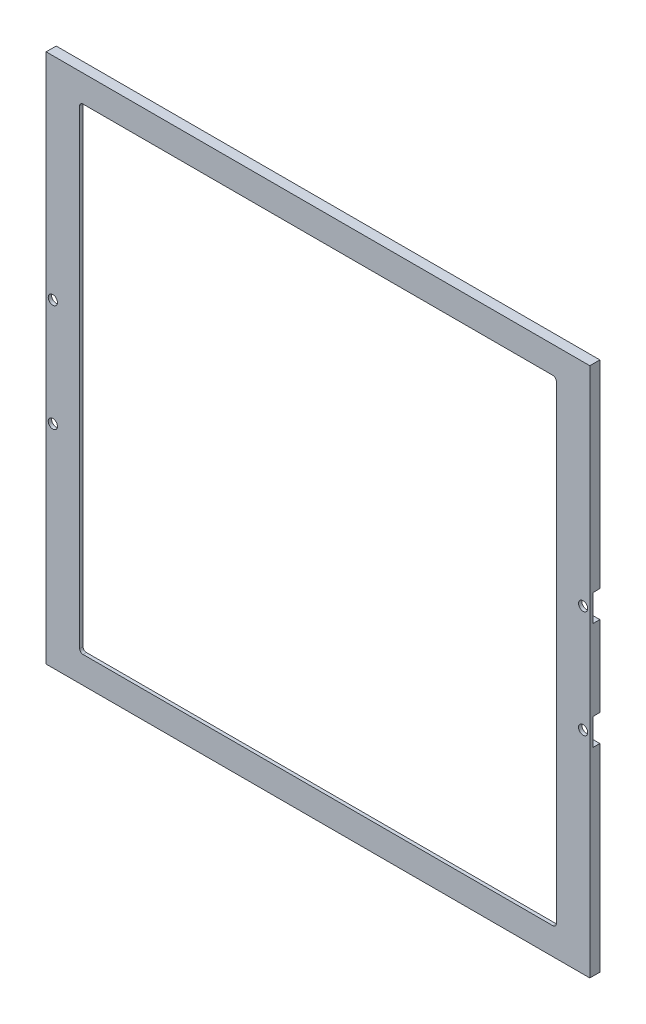
SolidWorks part; units mm, degrees
ref_plane "Front Plane" through (0, 0, 0) normal (0, 0, 1) x (1, 0, 0)
ref_plane "Top Plane" through (0, 0, 0) normal (0, 1, 0) x (1, 0, 0)
ref_plane "Right Plane" through (0, 0, 0) normal (1, 0, 0) x (0, 0, -1)
sketch "Sketch1" plane through (0, 0, 0) normal (0, 0, 1) x (1, 0, 0)
  line L0 (-238.335, 238.335) -> (-238.335, -238.335)
  line L1 (-238.335, -238.335) -> (238.335, -238.335)
  line L2 (238.335, -238.335) -> (238.335, 238.335)
  line L3 (238.335, 238.335) -> (-238.335, 238.335)
  line L4 (237.7, 237.7) -> (-237.7, 237.7)
  line L5 (-237.7, 237.7) -> (-237.7, -237.7)
  line L6 (-237.7, -237.7) -> (237.7, -237.7)
  line L7 (237.7, -237.7) -> (237.7, 237.7)
  line L8 (237.7, 237.7) -> (-237.7, 237.7) construction
  line L9 (-237.7, 237.7) -> (-237.7, -237.7) construction
  line L10 (-237.7, -237.7) -> (237.7, -237.7) construction
  line L11 (237.7, -237.7) -> (237.7, 237.7) construction
  line L12 (251.035, 251.035) -> (-251.035, 251.035)
  line L13 (-251.035, 251.035) -> (-251.035, -251.035)
  line L14 (-251.035, -251.035) -> (251.035, -251.035)
  line L15 (251.035, -251.035) -> (251.035, 251.035)
  dimension "D1" = 0
  dimension "D2" = 0.635
  dimension "D3" = 12.7
extrude "Extrude1" add sketch "Sketch1" against normal blind 6.35
sketch "Sketch2" plane through (0, 0, 0) normal (0, 0, 1) x (1, 0, 0)
  line L0 (251.035, 251.035) -> (-251.035, 251.035) construction
  line L1 (251.035, -251.035) -> (251.035, 251.035) construction
  line L2 (-251.035, -251.035) -> (251.035, -251.035) construction
  line L3 (-251.035, 251.035) -> (-251.035, -251.035) construction
  line L4 (251.035, 251.035) -> (-251.035, 251.035)
  line L5 (251.035, -251.035) -> (251.035, 251.035)
  line L6 (-251.035, -251.035) -> (251.035, -251.035)
  line L7 (-251.035, 251.035) -> (-251.035, -251.035)
  line L8 (-225.635, 225.635) -> (-225.635, -225.635)
  line L9 (-225.635, -225.635) -> (225.635, -225.635)
  line L10 (225.635, -225.635) -> (225.635, 225.635)
  line L11 (225.635, 225.635) -> (-225.635, 225.635)
  dimension "D1" = 25.4
extrude "Extrude2" add sketch "Sketch2" along normal blind 3.175
sketch "Sketch7" plane through (0, 0, 3.175) normal (0, 0, 1) x (1, 0, 0)
  line L0 (-251.035, -251.035) -> (251.035, -251.035) construction
  line L1 (-251.035, 251.035) -> (-257.385, 251.035)
  line L2 (-251.035, 251.035) -> (-251.035, -251.035)
  line L3 (-251.035, -251.035) -> (-257.385, -251.035)
  line L4 (-257.385, 251.035) -> (-257.385, -251.035)
  dimension "D1" = 6.35
extrude "Extrude3" add sketch "Sketch7" against normal up to surface (9.525 mm away) up to face at (0, 0, -6.35)
mirror "Mirror1" about plane through (0, 0, 0) normal (1, 0, 0) of "Extrude3"
hole_wizard "5/16 Clearance Hole1" positions "Sketch6" profile "Sketch5" hole size "5/16" standard "Ansi Inch" end condition through all
sketch "Sketch6" plane through (0, 0, 3.175) normal (0, 0, 1) x (1, 0, 0)
  line L0 (251.035, 0) -> (-251.035, 0) construction
  line L3 (251.035, -50.8) -> (251.035, 50.8) construction
  line L4 (-251.035, -50.8) -> (-251.035, 50.8) construction
  line L5 (-225.635, 225.635) -> (-225.635, -225.635) construction
  line L6 (225.635, -225.635) -> (225.635, 225.635) construction
  point P0 (251.035, -50.8)
  point P1 (251.035, 50.8)
  point P3 (-251.035, -50.8)
  point P5 (-251.035, 50.8)
  dimension "D1" = 25.4
  dimension "D2" = 25.4
  dimension "D3" = 50.8
  dimension "D4" = 101.6
  dimension "D5" = 50.8
  dimension "D6" = 101.6
sketch "Sketch5" plane through (251.035, -50.8, 3.175) normal (1, 0, 0) x (0, -1, 0)
  line L0 (0, 0) -> (0, 9.525)
  line L1 (0, 9.525) -> (4.365, 9.525)
  line L2 (4.365, 9.525) -> (4.365, 0)
  line L5 (4.365, 0) -> (0, 0)
  line L11 (0, -6.35) -> (0, 107.95) construction
  dimension "Thru Hole Dia." = 8.73
  dimension "Thru Hole Depth" = 9.525
sketch "Sketch8" plane through (0, 0, -6.35) normal (0, 0, -1) x (-1, 0, 0)
  line L0 (257.385, -251.035) -> (257.385, 251.035) construction
  line L1 (257.385, 63.5) -> (238.335, 63.5)
  line L2 (257.385, 63.5) -> (257.385, 38.1)
  line L3 (257.385, 38.1) -> (238.335, 38.1)
  line L4 (238.335, 63.5) -> (238.335, 38.1)
  line L5 (238.335, 50.8) -> (257.385, 50.8) construction
  line L6 (238.335, 238.335) -> (238.335, -238.335) construction
  point P8 (251.035, 50.8)
  dimension "D1" = 25.4
extrude "Cut-Extrude1" cut sketch "Sketch8" against normal blind 6.35
pattern_linear "LPattern1" count 2 spacing 101.6 along (0, -1, 0) of "Cut-Extrude1"
mirror "Mirror2" about plane through (0, 0, 0) normal (1, 0, 0) of "LPattern1", "Cut-Extrude1"
sketch "Sketch9" plane through (0, 0, 0) normal (0, 0, -1) x (-1, 0, 0)
  line L0 (-238.335, 238.335) -> (-235.16, 238.335)
  line L1 (-235.16, 238.335) -> (-235.16, 235.16)
  line L2 (0, 0) -> (0, 142.1036) construction
  line L3 (235.16, 238.335) -> (235.16, 235.16)
  line L4 (238.335, 238.335) -> (235.16, 238.335)
  line L5 (0, 0) -> (85.8683, 0) construction
  line L6 (238.335, -238.335) -> (235.16, -238.335)
  line L7 (235.16, -238.335) -> (235.16, -235.16)
  line L8 (-235.16, -238.335) -> (-235.16, -235.16)
  line L9 (-238.335, -238.335) -> (-235.16, -238.335)
  line L10 (-238.335, 238.335) -> (238.335, 238.335) construction
  line L11 (-238.335, 63.5) -> (-238.335, 238.335) construction
  arc A0 (-238.335, 238.335) -> (-235.16, 235.16) centre (-238.335, 235.16) ccw
  arc A1 (238.335, 238.335) -> (235.16, 235.16) centre (238.335, 235.16) cw
  arc A2 (238.335, -238.335) -> (235.16, -235.16) centre (238.335, -235.16) ccw
  arc A3 (-238.335, -238.335) -> (-235.16, -235.16) centre (-238.335, -235.16) cw
  dimension "D1" = 3.175
extrude "Extrude4" cut sketch "Sketch9" along normal through all
fillet "Fillet1" radius 3.175 4 edges at (225.635, -225.635, 1.5875) (-225.635, -225.635, 1.5875) (-225.635, 225.635, 1.5875) (225.635, 225.635, 1.5875)
